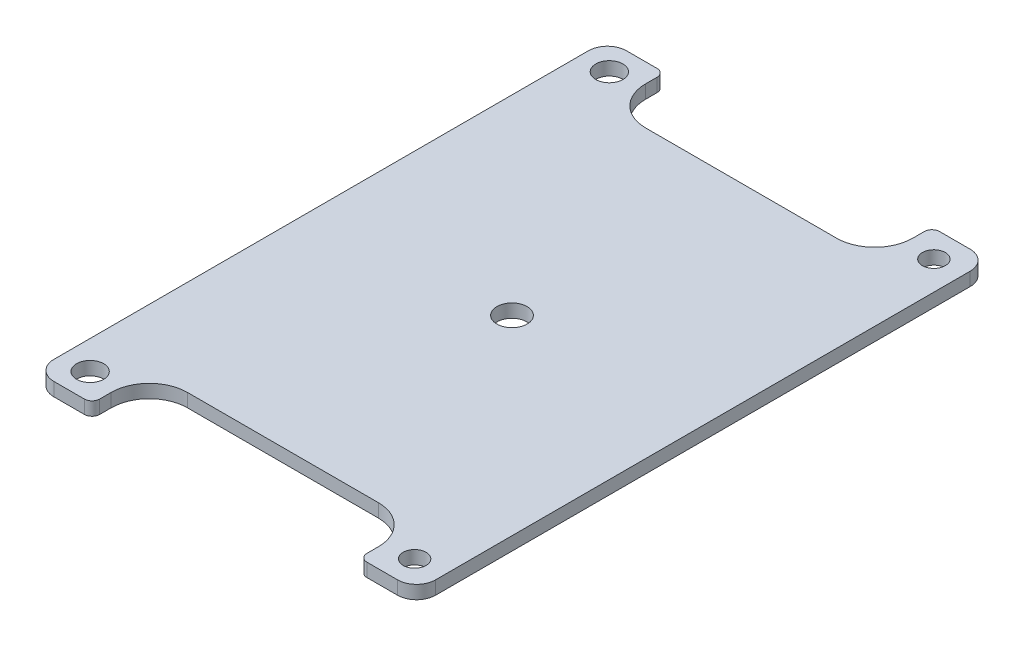
SolidWorks part; units mm, degrees
ref_plane "Front Plane" through (0, 0, 0) normal (0, 0, 1) x (1, 0, 0)
ref_plane "Top Plane" through (0, 0, 0) normal (0, 1, 0) x (1, 0, 0)
ref_plane "Right Plane" through (0, 0, 0) normal (1, 0, 0) x (0, 0, -1)
sketch "Sketch1" plane through (0, 0, 0) normal (0, 1, 0) x (1, 0, 0)
  line L0 (-25, 60) -> (25, 60)
  line L1 (-45, 75) -> (-37, 75)
  line L2 (-50, 70) -> (-50, -70)
  line L3 (-45, -75) -> (-37, -75)
  line L4 (50, 70) -> (50, -70)
  line L5 (-50, 75) -> (50, -75) construction
  line L6 (-50, -75) -> (50, 75) construction
  line L8 (-25, -60) -> (25, -60)
  line L10 (-35, 70) -> (-35, 73)
  line L11 (35, 70) -> (35, 73)
  line L12 (-35, -70) -> (-35, -73)
  line L13 (35, -70) -> (35, -73)
  line L14 (37, 75) -> (45, 75)
  line L15 (35, 60) -> (35, -60) construction
  line L16 (-50, 75) -> (50, 75) construction
  line L17 (-35, 60) -> (-35, -60) construction
  line L18 (37, -75) -> (45, -75)
  line L19 (-50, -75) -> (50, -75) construction
  line L20 (-35, -60) -> (35, -60) construction
  line L21 (-35, 60) -> (35, 60) construction
  line L22 (50, 75) -> (50, -75) construction
  line L23 (-50, 75) -> (-50, -75) construction
  line L24 (0, 0) -> (33.1777, 0) construction
  circle A0 centre (0, 0) radius 3.9688
  arc A1 (35, -70) -> (25, -60) centre (25, -70) ccw
  arc A2 (-25, -60) -> (-35, -70) centre (-25, -70) ccw
  arc A3 (25, 60) -> (35, 70) centre (25, 70) ccw
  arc A4 (-25, 60) -> (-35, 70) centre (-25, 70) cw
  arc A5 (45, -75) -> (50, -70) centre (45, -70) ccw
  arc A6 (-50, -70) -> (-45, -75) centre (-45, -70) ccw
  arc A7 (45, 75) -> (50, 70) centre (45, 70) cw
  arc A8 (-45, 75) -> (-50, 70) centre (-45, 70) ccw
  arc A9 (35, 73) -> (37, 75) centre (37, 73) cw
  arc A10 (-35, 73) -> (-37, 75) centre (-37, 73) ccw
  arc A11 (35, -73) -> (37, -75) centre (37, -73) ccw
  arc A12 (-35, -73) -> (-37, -75) centre (-37, -73) cw
  circle A13 centre (42.5, -68) radius 3
  circle A14 centre (-42.5, -68) radius 3.5484
  circle A15 centre (42.5, 68) radius 3
  circle A16 centre (-42.5, 68) radius 3.5484
  point P0 (0, 0)
  point P42 (35, 75)
  point P47 (35, -75)
  dimension "D2" = 10
  dimension "D3" = 5
  dimension "D4" = 2
  dimension "D5" = 7.5
  dimension "D1" = 15
  dimension "D6" = 7
  dimension "D7" = 7.5
extrude "Boss-Extrude1" add sketch "Sketch1" along normal blind 3.5 contours L2 A6 L3 A12 L12 A2 L8 A1 L13 A11 L18 A5 L4 A7 L14 A9 L11 A3 L0 A4 L10 A10 L1 A8
sketch "Sketch2" plane through (0, 0, 0) normal (0, -1, 0) x (1, 0, 0)
  circle A0 centre (0, 0) radius 3.9688 construction
  circle A1 centre (42.5, -68) radius 3 construction
  circle A2 centre (-42.5, -68) radius 3.5484 construction
  circle A3 centre (42.5, 68) radius 3 construction
  circle A4 centre (-42.5, 68) radius 3.5484 construction
  circle A5 centre (0, 0) radius 3.9688
  circle A6 centre (42.5, -68) radius 3
  circle A7 centre (-42.5, -68) radius 3.5484
  circle A8 centre (42.5, 68) radius 3
  circle A9 centre (-42.5, 68) radius 3.5484
extrude "Cut-Extrude3" cut sketch "Sketch2" against normal blind 6
